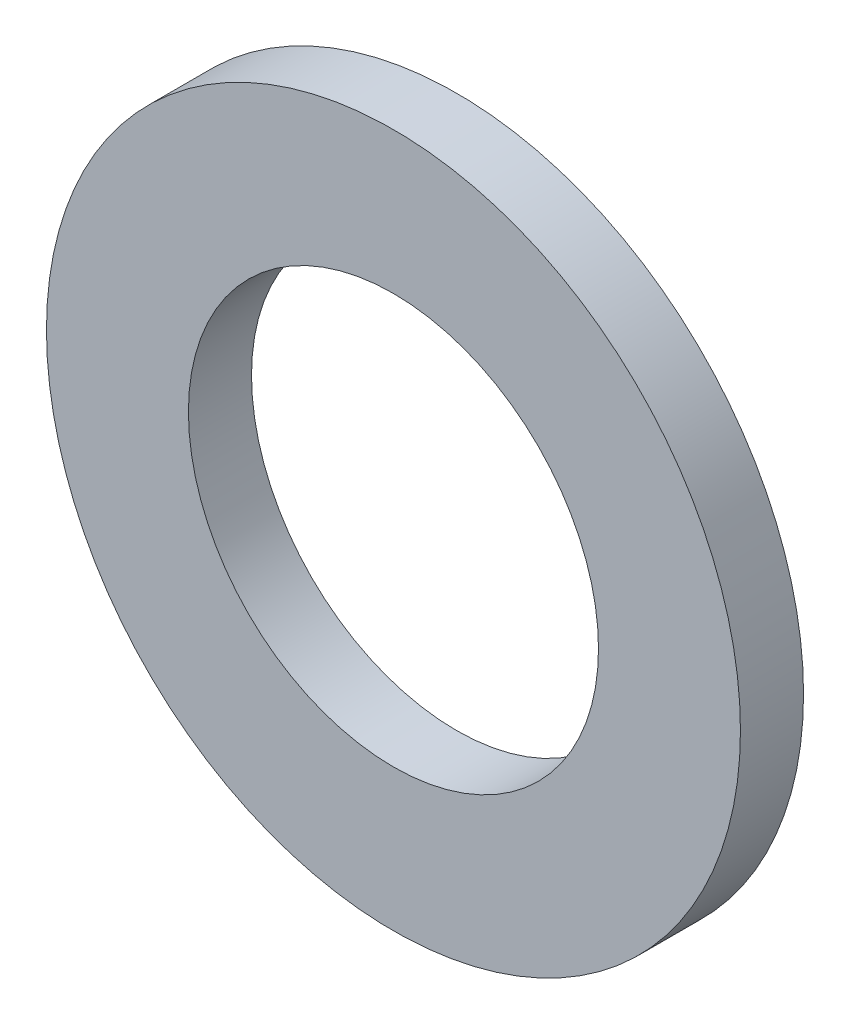
SolidWorks part; units mm, degrees
ref_plane "Plan de face" through (0, 0, 0) normal (0, 0, 1) x (1, 0, 0)
ref_plane "Plan de dessus" through (0, 0, 0) normal (0, 1, 0) x (1, 0, 0)
ref_plane "Plan de droite" through (0, 0, 0) normal (1, 0, 0) x (0, 0, -1)
sketch "Esquisse1" plane through (0, 0, 0) normal (0, 0, 1) x (1, 0, 0)
  circle A0 centre (0, 0) radius 22
  circle A1 centre (0, 0) radius 13
  dimension "D1" = 44
  dimension "D2" = 26
extrude "Boss.-Extru.1" add sketch "Esquisse1" along normal blind 4 contours A0 A1
